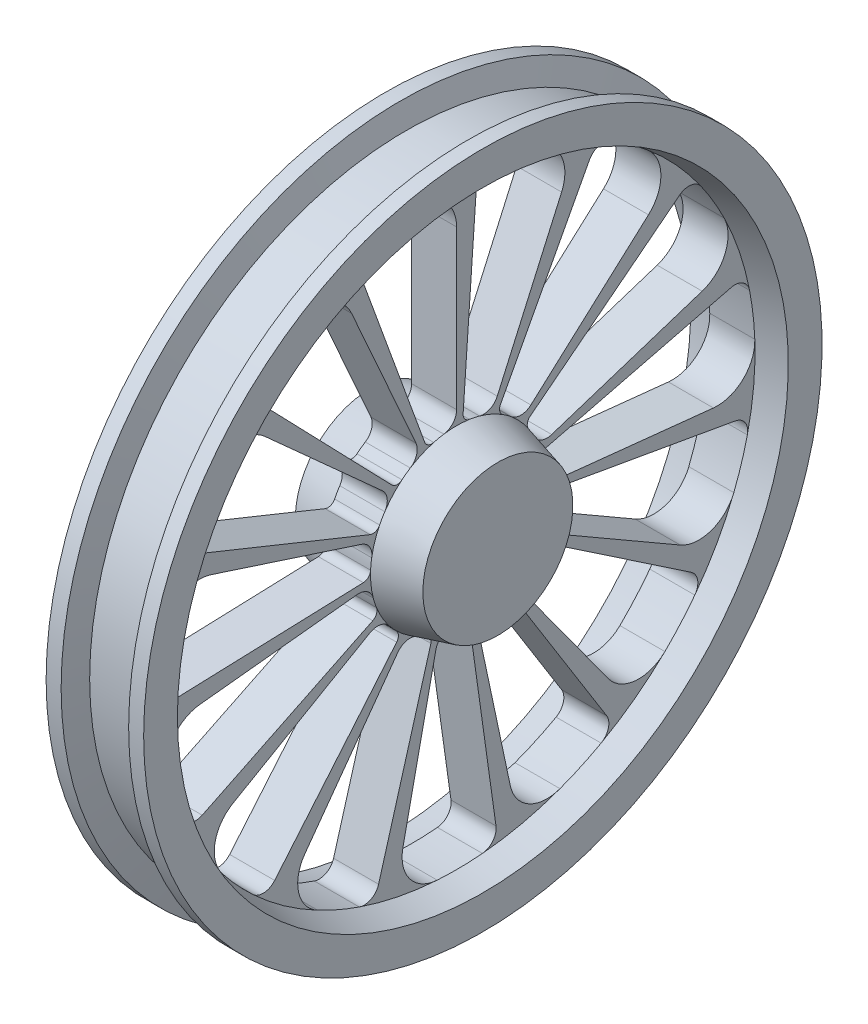
SolidWorks part; units mm, degrees
material "1060 Alloy"
ref_plane "Front Plane" through (0, 0, 0) normal (0, 0, 1) x (1, 0, 0)
ref_plane "Top Plane" through (0, 0, 0) normal (0, 1, 0) x (1, 0, 0)
ref_plane "Right Plane" through (0, 0, 0) normal (1, 0, 0) x (0, 0, -1)
sketch "Sketch1" plane through (0, 0, 0) normal (0, 1, 0) x (1, 0, 0)
  line L0 (-565.7846, 0) -> (565.7846, 0) construction
  line L1 (0, 565.7846) -> (0, -565.7846) construction
  line L2 (-85, 0) -> (85, 0)
  line L3 (85, 0) -> (85, 100)
  line L4 (85, 100) -> (30, 114.7372)
  line L5 (30, 114.7372) -> (30, 397.7628)
  line L6 (30, 397.7628) -> (65, 407.141)
  line L7 (-85, 0) -> (-85, 100)
  line L8 (45, 452.141) -> (36.9615, 422.141)
  line L9 (36.9615, 422.141) -> (-36.9615, 422.141)
  line L10 (45, 452.141) -> (65, 452.141)
  line L11 (-85, 100) -> (-30, 114.7372)
  line L12 (65, 452.141) -> (65, 407.141)
  line L13 (-30, 114.7372) -> (-30, 397.7628)
  line L14 (-30, 397.7628) -> (-65, 407.141)
  line L15 (-65, 452.141) -> (-65, 407.141)
  line L16 (-45, 452.141) -> (-65, 452.141)
  line L17 (-45, 452.141) -> (-36.9615, 422.141)
  point P3 (0, 0)
  point P4 (0, 0)
  point P8 (0, 0)
  point P14 (0, 0)
  point P26 (0, 422.141)
  dimension "D1" = 85
  dimension "D3" = 100
  dimension "D5" = 30
  dimension "D2" = 65
  dimension "D6" = 20
  dimension "D7" = 45
  dimension "D8" = 15
  dimension "D9" = 452.141
  dimension "D4" = 15
  dimension "D10" = 30
revolve "Revolve1" add sketch "Sketch1" angle 360 about L0
sketch "Sketch2" plane through (-85, 0, 0) normal (-1, 0, 0) x (0, 0, 1)
  line L0 (0, 0) -> (0, 397.7628) construction
  line L1 (0, 0) -> (136.0429, 373.7748) construction
  line L2 (0, 133.2446) -> (0, 344.1496)
  line L3 (42.5253, 116.8374) -> (129.0213, 354.4831)
  line L4 (54.1954, 121.725) -> (139.9783, 314.3963)
  line L5 (86.3708, 89.4396) -> (262.0481, 271.3587)
  line L6 (99.02, 89.158) -> (255.753, 230.281)
  line L7 (115.2821, 46.577) -> (349.7643, 141.314)
  line L8 (126.7231, 41.1748) -> (327.3057, 106.3481)
  line L9 (124.26, -4.3393) -> (377.0032, -13.1652)
  line L10 (132.5146, -13.9278) -> (342.2643, -35.9734)
  line L11 (111.7522, -54.5052) -> (339.0548, -165.3681)
  line L12 (115.3932, -66.6223) -> (298.0423, -172.0748)
  line L13 (79.9215, -95.2467) -> (242.4807, -288.9772)
  line L14 (78.3192, -107.7971) -> (202.2861, -278.4229)
  line L15 (34.2716, -119.5192) -> (103.9795, -362.6196)
  line L16 (27.7031, -130.3329) -> (71.5527, -336.6291)
  line L17 (-17.3042, -123.1257) -> (-52.5007, -373.5618)
  line L18 (-27.7031, -130.3329) -> (-71.5527, -336.6291)
  line L19 (-65.8879, -105.4427) -> (-199.903, -319.9117)
  line L20 (-78.3192, -107.7971) -> (-202.2861, -278.4229)
  line L21 (-103.079, -69.5277) -> (-312.7403, -210.946)
  line L22 (-115.3932, -66.6223) -> (-298.0423, -172.0748)
  line L23 (-122.4468, -21.5907) -> (-371.502, -65.5058)
  line L24 (-132.5146, -13.9278) -> (-342.2643, -35.9734)
  line L25 (-120.6424, 30.0795) -> (-366.0276, 91.2609)
  line L26 (-126.7231, 41.1748) -> (-327.3057, 106.3481)
  line L27 (-97.9779, 76.5487) -> (-297.2637, 232.2478)
  line L28 (-99.02, 89.158) -> (-255.753, 230.281)
  line L29 (-58.3721, 109.7819) -> (-177.1002, 333.077)
  line L30 (-54.1954, 121.725) -> (-139.9783, 314.3963)
  line L31 (-8.6732, 124.0328) -> (-26.3144, 376.3141)
  circle A0 centre (0, 0) radius 397.7628 construction
  circle A1 centre (0, 0) radius 114.7372 construction
  arc A2 (116.0632, 380.4531) -> (57.1888, 393.6301) centre (0, 0) ccw
  arc A3 (30.4725, 110.6167) -> (17.0313, 113.4661) centre (0, 0) ccw
  arc A4 (42.5253, 116.8374) -> (30.4725, 110.6167) centre (33.1284, 120.2576) cw
  arc A5 (17.0313, 113.4661) -> (0, 133.2446) centre (20, 133.2446) cw
  arc A6 (129.0213, 354.4831) -> (116.0632, 380.4531) centre (110.2274, 361.3235) ccw
  arc A7 (0, 344.1496) -> (57.1888, 393.6301) centre (50, 344.1496) cw
  arc A8 (72.8299, 88.6591) -> (61.7097, 96.7292) centre (0, 0) ccw
  arc A9 (61.7097, 96.7292) -> (54.1954, 121.725) centre (72.4664, 113.5902) cw
  arc A10 (86.3708, 89.4396) -> (72.8299, 88.6591) centre (79.1774, 96.3862) cw
  arc A11 (139.9783, 314.3963) -> (212.3484, 336.3382) centre (185.6555, 294.0595) cw
  arc A12 (260.7733, 300.354) -> (212.3484, 336.3382) centre (0, 0) ccw
  arc A13 (262.0481, 271.3587) -> (260.7733, 300.354) centre (247.6613, 285.2519) ccw
  arc A14 (102.5943, 51.3715) -> (95.7179, 63.267) centre (0, 0) ccw
  arc A15 (95.7179, 63.267) -> (99.02, 89.158) centre (112.4026, 74.2951) cw
  arc A16 (115.2821, 46.577) -> (102.5943, 51.3715) centre (111.536, 55.8488) cw
  arc A17 (255.753, 230.281) -> (330.791, 220.8904) centre (289.2095, 193.1238) cw
  arc A18 (360.3932, 168.321) -> (330.791, 220.8904) centre (0, 0) ccw
  arc A19 (349.7643, 141.314) -> (360.3932, 168.321) centre (342.2722, 159.8576) ccw
  arc A20 (114.6193, 5.2013) -> (113.1757, 18.8653) centre (0, 0) ccw
  arc A21 (113.1757, 18.8653) -> (126.7231, 41.1748) centre (132.9035, 22.1537) cw
  arc A22 (124.26, -4.3393) -> (114.6193, 5.2013) centre (124.609, 5.6547) cw
  arc A23 (327.3057, 106.3481) -> (392.0368, 67.2486) centre (342.7566, 58.7953) cw
  arc A24 (397.6979, 7.1838) -> (392.0368, 67.2486) centre (0, 0) ccw
  arc A25 (377.0032, -13.1652) -> (397.6979, 7.1838) centre (377.7012, 6.8226) ccw
  arc A26 (106.8255, -41.8682) -> (111.0643, -28.7984) centre (0, 0) ccw
  arc A27 (111.0643, -28.7984) -> (132.5146, -13.9278) centre (130.4241, -33.8183) cw
  arc A28 (111.7522, -54.5052) -> (106.8255, -41.8682) centre (116.1359, -45.5173) cw
  arc A29 (342.2643, -35.9734) -> (385.4959, -98.0211) centre (337.0379, -85.6995) cw
  arc A30 (366.237, -155.1956) -> (385.4959, -98.0211) centre (0, 0) ccw
  arc A31 (339.0548, -165.3681) -> (366.237, -155.1956) centre (347.8222, -147.3922) ccw
  arc A32 (80.5606, -81.6983) -> (89.7489, -71.4826) centre (0, 0) ccw
  arc A33 (89.7489, -71.4826) -> (115.3932, -66.6223) centre (105.3932, -83.9428) cw
  arc A34 (79.9215, -95.2467) -> (80.5606, -81.6983) centre (87.5819, -88.8188) cw
  arc A35 (298.0423, -172.0748) -> (312.2993, -246.342) centre (273.0423, -215.3761) cw
  arc A36 (271.4504, -290.7403) -> (312.2993, -246.342) centre (0, 0) ccw
  arc A37 (242.4807, -288.9772) -> (271.4504, -290.7403) centre (257.8016, -276.1215) ccw
  arc A38 (40.3661, -107.4021) -> (52.9151, -101.8067) centre (0, 0) ccw
  arc A39 (52.9151, -101.8067) -> (78.3192, -107.7971) centre (62.1389, -119.5528) cw
  arc A40 (34.2716, -119.5192) -> (40.3661, -107.4021) centre (43.8842, -116.7628) cw
  arc A41 (202.2861, -278.4229) -> (185.1033, -352.0682) centre (161.8352, -307.8122) cw
  arc A42 (129.7276, -376.0133) -> (185.1033, -352.0682) centre (0, 0) ccw
  arc A43 (103.9795, -362.6196) -> (129.7276, -376.0133) centre (123.2047, -357.1069) ccw
  arc A44 (-6.8081, -114.535) -> (6.9319, -114.5276) centre (0, 0) ccw
  arc A45 (6.9319, -114.5276) -> (27.7031, -130.3329) centre (8.1402, -134.4911) cw
  arc A46 (-17.3042, -123.1257) -> (-6.8081, -114.535) centre (-7.4015, -124.5174) cw
  arc A47 (71.5527, -336.6291) -> (25.9012, -396.9186) centre (22.6453, -347.0247) cw
  arc A48 (-34.4263, -396.2702) -> (25.9012, -396.9186) centre (0, 0) ccw
  arc A49 (-52.5007, -373.5618) -> (-34.4263, -396.2702) centre (-32.6953, -376.3452) ccw
  arc A50 (-52.8051, -101.8638) -> (-40.25, -107.4456) centre (0, 0) ccw
  arc A51 (-40.25, -107.4456) -> (-27.7031, -130.3329) centre (-47.2661, -126.1746) cw
  arc A52 (-65.8879, -105.4427) -> (-52.8051, -101.8638) centre (-57.4074, -110.7419) cw
  arc A53 (-71.5527, -336.6291) -> (-137.7794, -373.1381) centre (-120.4601, -326.2335) cw
  arc A54 (-192.6276, -348.0084) -> (-137.7794, -373.1381) centre (0, 0) ccw
  arc A55 (-199.903, -319.9117) -> (-192.6276, -348.0084) centre (-182.9421, -330.5101) ccw
  arc A56 (-89.6717, -71.5795) -> (-80.4723, -81.7853) centre (0, 0) ccw
  arc A57 (-80.4723, -81.7853) -> (-78.3192, -107.7971) centre (-94.4995, -96.0414) cw
  arc A58 (-103.079, -69.5277) -> (-89.6717, -71.5795) centre (-97.4871, -77.818) cw
  arc A59 (-202.2861, -278.4229) -> (-277.6367, -284.8387) centre (-242.7369, -249.0336) cw
  arc A60 (-317.5219, -239.5728) -> (-277.6367, -284.8387) centre (0, 0) ccw
  arc A61 (-312.7403, -210.946) -> (-317.5219, -239.5728) centre (-301.5565, -227.5268) ccw
  arc A62 (-111.0331, -28.9183) -> (-106.7802, -41.9836) centre (0, 0) ccw
  arc A63 (-106.7802, -41.9836) -> (-115.3932, -66.6223) centre (-125.3932, -49.3018) cw
  arc A64 (-122.4468, -21.5907) -> (-111.0331, -28.9183) centre (-120.7103, -31.4387) cw
  arc A65 (-298.0423, -172.0748) -> (-369.4881, -147.2881) centre (-323.0423, -128.7735) cw
  arc A66 (-387.5137, -89.7128) -> (-369.4881, -147.2881) centre (0, 0) ccw
  arc A67 (-371.502, -65.5058) -> (-387.5137, -89.7128) centre (-368.029, -85.202) ccw
  arc A68 (-113.196, 18.743) -> (-114.6248, 5.0775) centre (0, 0) ccw
  arc A69 (-114.6248, 5.0775) -> (-132.5146, -13.9278) centre (-134.6052, 5.9626) cw
  arc A70 (-120.6424, 30.0795) -> (-113.196, 18.743) centre (-123.0616, 20.3766) cw
  arc A71 (-342.2643, -35.9734) -> (-397.4516, 15.73) centre (-347.4908, 13.7527) cw
  arc A72 (-390.5009, 75.6592) -> (-397.4516, 15.73) centre (0, 0) ccw
  arc A73 (-366.0276, 91.2609) -> (-390.5009, 75.6592) centre (-370.866, 71.855) ccw
  arc A74 (-95.7862, 63.1635) -> (-102.6498, 51.2607) centre (0, 0) ccw
  arc A75 (-102.6498, 51.2607) -> (-126.7231, 41.1748) centre (-120.5428, 60.196) cw
  arc A76 (-97.9779, 76.5487) -> (-95.7862, 63.1635) centre (-104.1345, 68.6686) cw
  arc A77 (-327.3057, 106.3481) -> (-356.6922, 176.0282) centre (-311.8549, 153.9009) cw
  arc A78 (-325.9669, 227.9492) -> (-356.6922, 176.0282) centre (0, 0) ccw
  arc A79 (-297.2637, 232.2478) -> (-325.9669, 227.9492) centre (-309.5769, 216.4876) ccw
  arc A80 (-61.8141, 96.6625) -> (-72.9256, 88.5804) centre (0, 0) ccw
  arc A81 (-72.9256, 88.5804) -> (-99.02, 89.158) centre (-85.6374, 104.0209) cw
  arc A82 (-58.3721, 109.7819) -> (-61.8141, 96.6625) centre (-67.2016, 105.0872) cw
  arc A83 (-255.753, 230.281) -> (-254.2574, 305.8895) centre (-222.2965, 267.4383) cw
  arc A84 (-205.0703, 340.8246) -> (-254.2574, 305.8895) centre (0, 0) ccw
  arc A85 (-177.1002, 333.077) -> (-205.0703, 340.8246) centre (-194.7591, 323.6875) ccw
  arc A86 (-17.1538, 113.4477) -> (-30.592, 110.5837) centre (0, 0) ccw
  arc A87 (-30.592, 110.5837) -> (-54.1954, 121.725) centre (-35.9245, 129.8597) cw
  arc A88 (-8.6732, 124.0328) -> (-17.1538, 113.4477) centre (-18.6489, 123.3353) cw
  arc A89 (-139.9783, 314.3963) -> (-107.8592, 382.8598) centre (-94.301, 334.7332) cw
  arc A90 (-48.7152, 394.7684) -> (-107.8592, 382.8598) centre (0, 0) ccw
  arc A91 (-26.3144, 376.3141) -> (-48.7152, 394.7684) centre (-46.2657, 374.9189) ccw
  point P9 (39.2424, 107.8177)
  point P12 (0, 114.7372)
  point P190 (0, 0)
  dimension "D2" = 10
  dimension "D3" = 20
  dimension "D4" = 20
  dimension "D5" = 50
  dimension "D1" = 20
  dimension "D6" = 15
extrude "Cut-Extrude1" cut sketch "Sketch2" against normal through all
equation "\"a\"= 130mm"
equation "\"b\"= 915mm"
equation "\"D1@Sketch1\"=(\"a\"+40)/2"
equation "\"D2@Sketch1\"=\"a\"/2"
